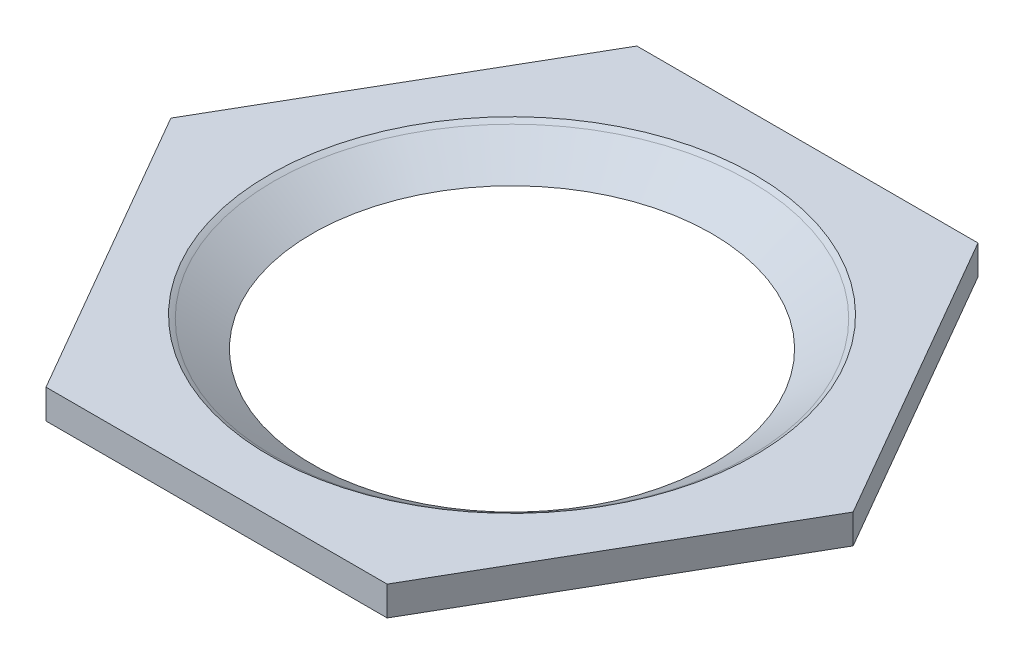
SolidWorks part; units mm, degrees
ref_plane "Front Plane" through (0, 0, 0) normal (0, 0, 1) x (1, 0, 0)
ref_plane "Top Plane" through (0, 0, 0) normal (0, 1, 0) x (1, 0, 0)
ref_plane "Right Plane" through (0, 0, 0) normal (1, 0, 0) x (0, 0, -1)
ref_plane "Plane_hex_bottom" through (0, 64.4906, 0) normal (0, 1, 0) x (1, 0, 0)
sketch "Sk_hex" plane through (0, 64.4906, 0) normal (0, 1, 0) x (1, 0, 0)
  line L0 (22.1437, 0) -> (11.0718, -19.177)
  line L1 (11.0718, -19.177) -> (-11.0718, -19.177)
  line L2 (-11.0718, -19.177) -> (-22.1437, 0)
  line L3 (-22.1437, 0) -> (-11.0718, 19.177)
  line L4 (-11.0718, 19.177) -> (11.0718, 19.177)
  line L5 (11.0718, 19.177) -> (22.1437, 0)
extrude "Ext_hex" add sketch "Sk_hex" along normal blind 1.905
sketch "Sk_hex_bore" plane through (0, 0, 0) normal (0, 0, 1) x (1, 0, 0)
  line L0 (0, 64.008) -> (12.9718, 64.008)
  line L1 (12.9718, 64.008) -> (12.9718, 64.4906)
  line L2 (12.9718, 64.4906) -> (15.4572, 66.1949)
  line L3 (15.7683, 66.3956) -> (15.7683, 66.802)
  line L4 (15.7683, 66.802) -> (0, 66.802)
  line L5 (0, 66.802) -> (0, 64.008)
  line L6 (0, -25.4) -> (0, 76.2) construction
  arc A0 (15.4572, 66.1949) -> (15.7683, 66.3956) centre (19.1637, 60.7891) cw
revolve "Cut_hex_bore" cut sketch "Sk_hex_bore" angle 360 about L6
